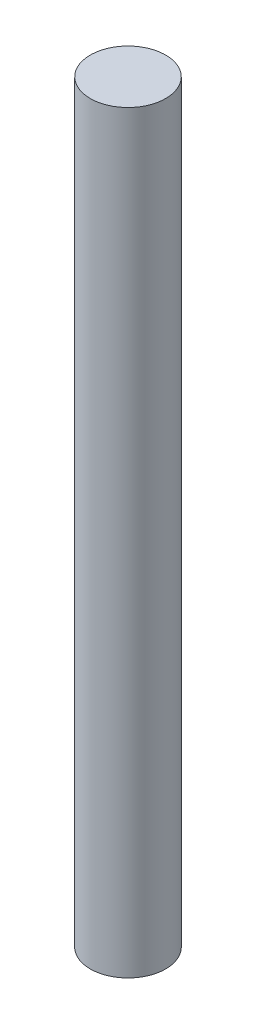
SolidWorks part; units mm, degrees
ref_plane "Спереди" through (0, 0, 0) normal (0, 0, 1) x (1, 0, 0)
ref_plane "Сверху" through (0, 0, 0) normal (0, 1, 0) x (1, 0, 0)
ref_plane "Справа" through (0, 0, 0) normal (1, 0, 0) x (0, 0, -1)
other "Configuration Table"
sketch "Эскиз1" plane through (0, 0, 0) normal (0, 1, 0) x (1, 0, 0)
  circle A0 centre (0, 0) radius 5
  dimension "D1" = 10
extrude "Бобышка-Вытянуть1" add sketch "Эскиз1" along normal blind 100
